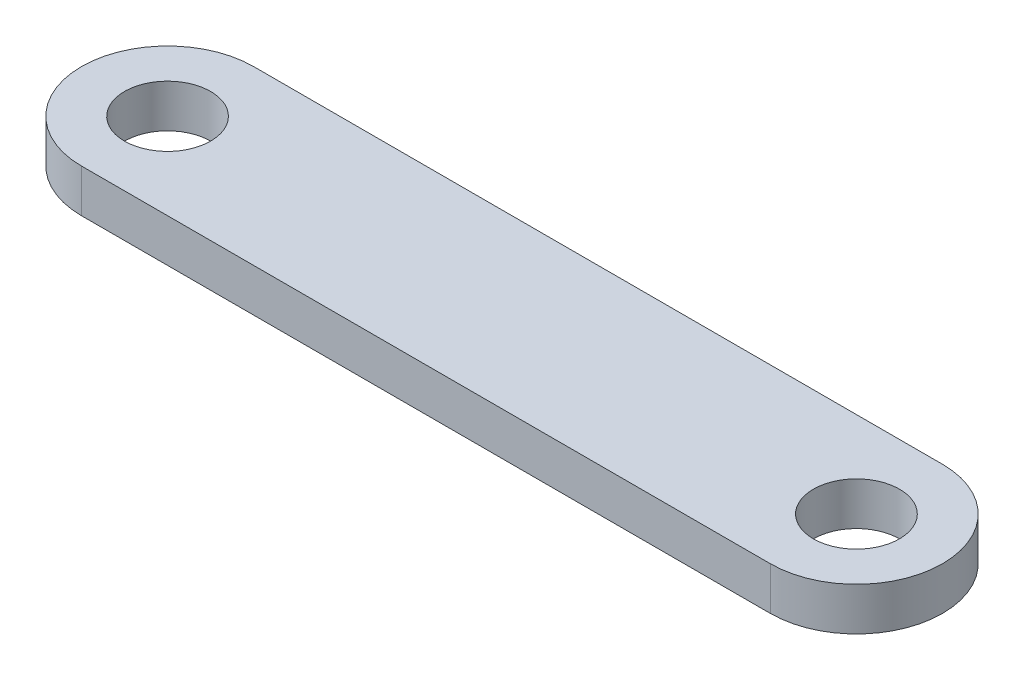
SolidWorks part; units mm, degrees
material "AISI 1035 Steel (SS)"
ref_plane "Front Plane" through (0, 0, 0) normal (0, 0, 1) x (1, 0, 0)
ref_plane "Top Plane" through (0, 0, 0) normal (0, 1, 0) x (1, 0, 0)
ref_plane "Right Plane" through (0, 0, 0) normal (1, 0, 0) x (0, 0, -1)
sketch "Sketch1" plane through (0, 0, 0) normal (0, 1, 0) x (1, 0, 0)
  line L0 (-16, 0) -> (16, 0) construction
  line L1 (-16, 4) -> (16, 4)
  line L2 (-16, -4) -> (16, -4)
  arc A0 (-16, 4) -> (-16, -4) centre (-16, 0) ccw
  arc A1 (16, -4) -> (16, 4) centre (16, 0) ccw
  circle A2 centre (-16, 0) radius 2
  circle A3 centre (16, 0) radius 2
  point P3 (0, 0)
  dimension "D1" = 4
  dimension "D2" = 32
  dimension "D3" = 4
extrude "Boss-Extrude1" add sketch "Sketch1" along normal mid plane 2
